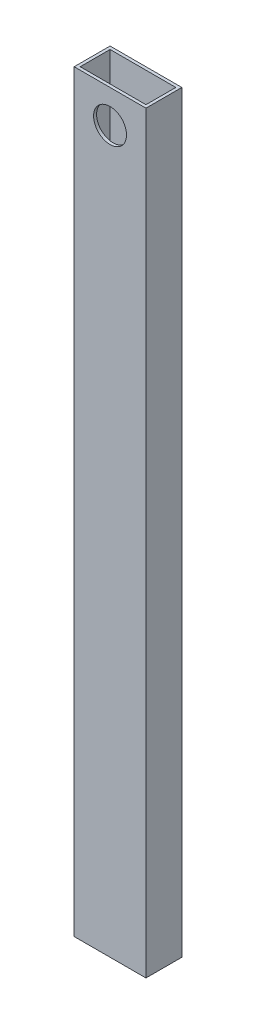
SolidWorks part; units mm, degrees
material "6063-T6"
ref_plane "Front Plane" through (0, 0, 0) normal (0, 0, 1) x (1, 0, 0)
ref_plane "Top Plane" through (0, 0, 0) normal (0, 1, 0) x (1, 0, 0)
ref_plane "Right Plane" through (0, 0, 0) normal (1, 0, 0) x (0, 0, -1)
sketch "Sketch1" plane through (0, 0, 0) normal (0, 1, 0) x (1, 0, 0)
  line L1 (-38.1, 19.05) -> (38.1, 19.05)
  line L2 (-38.1, 19.05) -> (-38.1, -19.05)
  line L3 (-38.1, -19.05) -> (38.1, -19.05)
  line L4 (38.1, 19.05) -> (38.1, -19.05)
  line L5 (-38.1, 19.05) -> (38.1, -19.05) construction
  line L6 (-38.1, -19.05) -> (38.1, 19.05) construction
  point P0 (0, 0)
  dimension "D1" = 76.2
  dimension "D2" = 38.1
extrude "Extrude-Thin1" add sketch "Sketch1" along normal blind 510 and the other way blind 290 thin
hole_wizard "Ø12.0 (12) Diameter Hole1" positions "Sketch2" profile "Sketch3" hole size "Ø12.0" standard "ANSI Metric"
sketch "Sketch2" plane through (0, 0, -19.05) normal (0, 0, -1) x (-1, 0, 0)
  line L1 (-20, -25) -> (20, -25)
  line L2 (-20, -25) -> (-20, -275)
  line L3 (-20, -275) -> (20, -275)
  line L4 (20, -25) -> (20, -275)
  line L5 (0, 55) -> (0, -55) construction
  line L6 (-38.1, -290) -> (38.1, -290) construction
  point P1 (-20, -25)
  point P2 (20, -275)
  point P69 (-20, -275)
  point P70 (20, -25)
  point P71 (0, -275)
  dimension "D1" = 40
  dimension "D2" = 25
  dimension "D3" = 15
sketch "Sketch3" plane through (20, -25, -19.05) normal (1, 0, 0) x (0, 1, 0)
  line L0 (0, 0) -> (0, 3.175)
  line L1 (0, 3.175) -> (6, 3.175)
  line L2 (6, 3.175) -> (6, 0)
  line L5 (6, 0) -> (0, 0)
  line L11 (0, -6.35) -> (0, 107.95) construction
  dimension "Thru Hole Dia." = 12
  dimension "Thru Hole Depth" = 3.175
sketch "Sketch6" plane through (0, 0, 19.05) normal (0, 0, 1) x (1, 0, 0)
  line L0 (0, -55) -> (0, 55) construction
  line L1 (-38.1, 510) -> (38.1, 510) construction
  circle A0 centre (0, 475) radius 17.5
  dimension "D1" = 35
  dimension "D2" = 35
extrude "Cut-Extrude1" cut sketch "Sketch6" against normal up to next
sketch "Sketch7" plane through (0, 0, -19.05) normal (0, 0, -1) x (-1, 0, 0)
  line L0 (0, 55) -> (0, -55) construction
  circle A0 centre (0, -75) radius 17.5
  dimension "D1" = 35
  dimension "D2" = 75
extrude "Cut-Extrude2" cut sketch "Sketch7" against normal up to next
